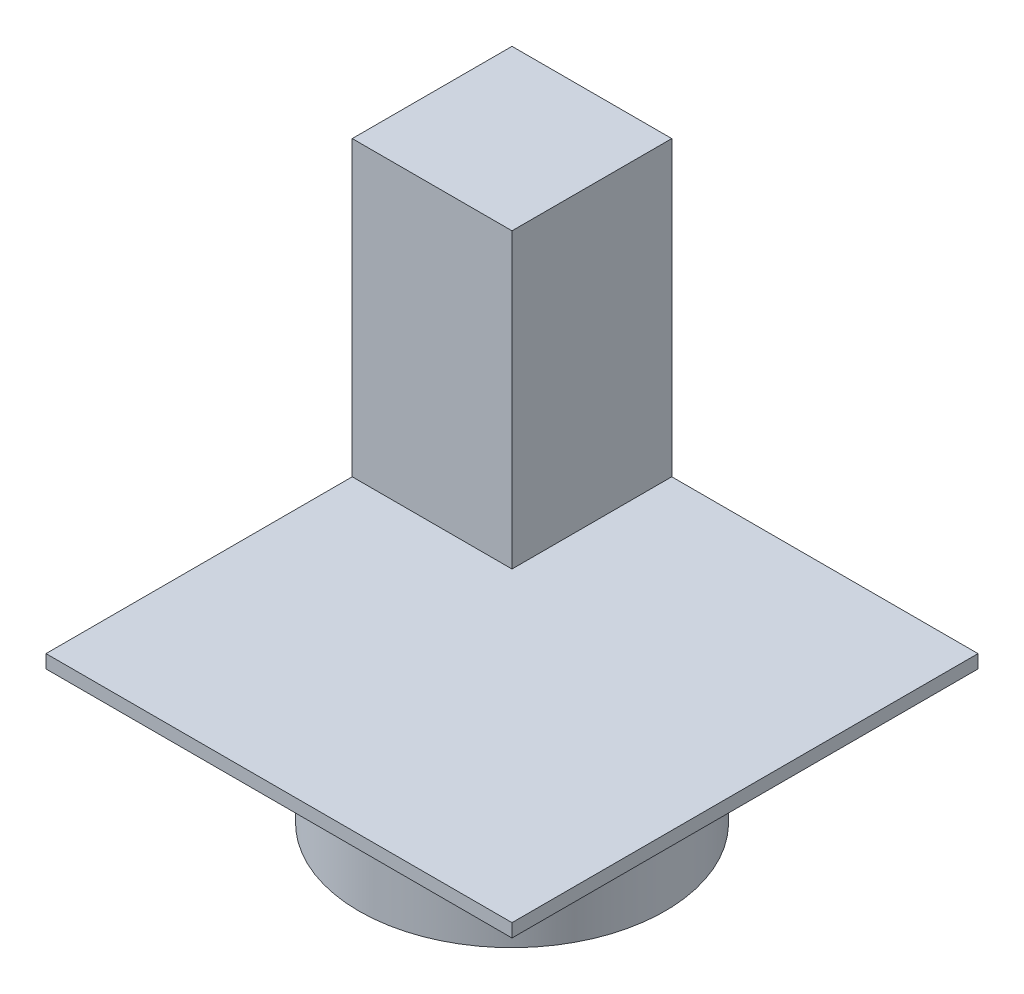
SolidWorks part; units mm, degrees
ref_plane "Front Plane" through (0, 0, 0) normal (0, 0, 1) x (1, 0, 0)
ref_plane "Top Plane" through (0, 0, 0) normal (0, 1, 0) x (1, 0, 0)
ref_plane "Right Plane" through (0, 0, 0) normal (1, 0, 0) x (0, 0, -1)
sketch "Sketch1" plane through (0, 0, 0) normal (0, 1, 0) x (1, 0, 0)
  line L1 (0, 0) -> (35, 0)
  line L2 (0, 0) -> (0, 35)
  line L3 (0, 35) -> (35, 35)
  line L4 (35, 0) -> (35, 35)
  dimension "D1" = 35
extrude "Boss-Extrude1" add sketch "Sketch1" along normal blind 1
sketch "Sketch2" plane through (0, 1, 0) normal (0, 1, 0) x (1, 0, 0)
  line L1 (0, 35) -> (12, 35)
  line L2 (0, 35) -> (0, 23)
  line L3 (0, 23) -> (12, 23)
  line L4 (12, 35) -> (12, 23)
  dimension "D1" = 12
extrude "Boss-Extrude2" add sketch "Sketch2" along normal blind 22
sketch "Sketch3" plane through (0, 0, 0) normal (0, -1, 0) x (1, 0, 0)
  line L0 (17.5, 0) -> (17.5, -35) construction
  line L1 (0, 0) -> (35, 0) construction
  line L2 (35, -35) -> (0, -35) construction
  line L3 (0, -17.5) -> (35, -17.5) construction
  line L4 (0, -35) -> (0, 0) construction
  line L5 (35, 0) -> (35, -35) construction
  circle A0 centre (17.5, -17.5) radius 11.5
  circle A1 centre (17.5, -17.5) radius 10.25
  dimension "D1" = 20.5
  dimension "D2" = 23
extrude "Boss-Extrude3" add sketch "Sketch3" along normal blind 10
